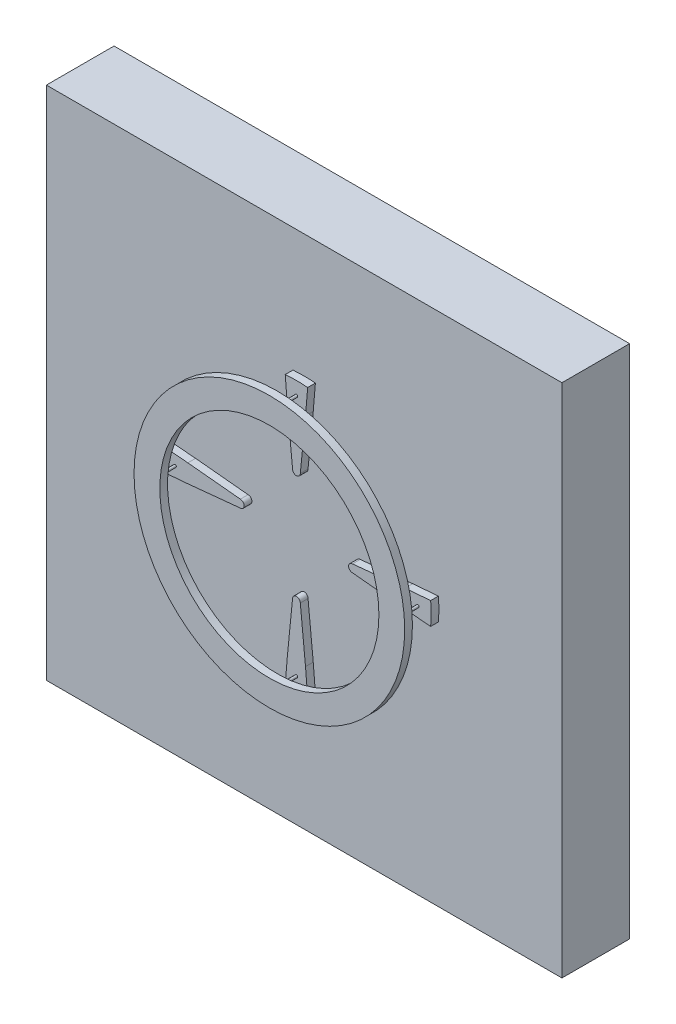
SolidWorks part; units mm, degrees
ref_plane "前基準面" through (0, 0, 0) normal (0, 0, 1) x (1, 0, 0)
ref_plane "上基準面" through (0, 0, 0) normal (0, 1, 0) x (1, 0, 0)
ref_plane "右基準面" through (0, 0, 0) normal (1, 0, 0) x (0, 0, -1)
sketch "草圖1" plane through (0, 0, 0) normal (0, 0, 1) x (1, 0, 0)
  line L0 (-0.03, 0.435) -> (-0.0704, 0.8425)
  line L1 (0, 0.435) -> (0, 0.8542) construction
  line L2 (0.03, 0.435) -> (0.0704, 0.8425)
  line L3 (0.435, 0.03) -> (0.8425, 0.0704)
  line L4 (0.435, -0.03) -> (0.8425, -0.0704)
  line L5 (0.03, -0.435) -> (0.0704, -0.8425)
  line L6 (-0.03, -0.435) -> (-0.0704, -0.8425)
  line L7 (-0.435, -0.03) -> (-0.8425, -0.0704)
  line L8 (-0.435, 0.03) -> (-0.8425, 0.0704)
  line L9 (-0.0704, 0.8425) -> (-0.087, 1.0414)
  line L10 (0.0704, 0.8425) -> (0.087, 1.0414)
  line L11 (0.8425, 0.0704) -> (1.0414, 0.087)
  line L12 (0.8425, -0.0704) -> (1.0414, -0.087)
  line L13 (-0.0704, -0.8425) -> (-0.087, -1.0414)
  line L14 (0.0704, -0.8425) -> (0.087, -1.0414)
  line L15 (-0.8425, 0.0704) -> (-1.0414, 0.087)
  line L16 (-0.8425, -0.0704) -> (-1.0414, -0.087)
  circle A0 centre (0, 0) radius 0.405
  arc A2 (-0.03, 0.435) -> (0.03, 0.435) centre (0, 0.435) ccw
  arc A4 (0.435, 0.03) -> (0.435, -0.03) centre (0.435, 0) ccw
  arc A6 (0.03, -0.435) -> (-0.03, -0.435) centre (0, -0.435) ccw
  arc A8 (-0.435, -0.03) -> (-0.435, 0.03) centre (-0.435, 0) ccw
  arc A9 (0.0704, 0.8425) -> (-0.0704, 0.8425) centre (0, 0) ccw
  arc A10 (0.087, 1.0414) -> (-0.087, 1.0414) centre (0, 0) ccw
  arc A11 (-1.0414, 0.087) -> (-1.0414, -0.087) centre (0, 0) ccw
  arc A12 (-0.8425, 0.0704) -> (-0.8425, -0.0704) centre (0, 0) ccw
  arc A13 (-0.0704, -0.8425) -> (0.0704, -0.8425) centre (0, 0) ccw
  arc A14 (-0.087, -1.0414) -> (0.087, -1.0414) centre (0, 0) ccw
  arc A15 (1.0414, -0.087) -> (1.0414, 0.087) centre (0, 0) ccw
  arc A16 (0.8425, -0.0704) -> (0.8425, 0.0704) centre (0, 0) ccw
  point P27 (0, 0)
  dimension "D1" = 5.66
  dimension "D2" = 4
extrude "填料-伸長1" add sketch "草圖1" along normal blind 0.06
sketch "草圖2" plane through (0, 0, 0.06) normal (0, 0, 1) x (1, 0, 0)
  line L0 (0.9419, 0.0787) -> (0.9419, -0.1053) construction
  line L1 (0.8425, 0.0704) -> (1.0414, 0.087) construction
  line L2 (1.05, 0) -> (0.6277, 0) construction
  line L3 (0.8425, -0.0704) -> (1.0414, -0.087) construction
  circle A0 centre (0, 0) radius 0.85
  circle A1 centre (0, 0) radius 1.05
  circle A3 centre (0.9419, 0) radius 0.07
  circle A4 centre (0, -0.9419) radius 0.07
  circle A5 centre (-0.9419, 0) radius 0.07
  circle A6 centre (0, 0.9419) radius 0.07
  circle A7 centre (0.9419, 0) radius 0.01
  circle A8 centre (0, -0.9419) radius 0.01
  circle A9 centre (-0.9419, 0) radius 0.01
  circle A10 centre (0, 0.9419) radius 0.01
  point P10 (0.9419, 0)
  point P11 (0.847, 0.0708)
  point P12 (0.847, -0.0708)
  point P26 (0, 0)
  point P34 (0, 0)
  dimension "D1" = 4
  dimension "D2" = 4
extrude "填料-伸長2" add sketch "草圖2" along normal blind 0.15 contours A7 | A10 | A9 | A8
sketch "草圖3" plane through (0, 0, 0.21) normal (0, 0, 1) x (1, 0, 0)
  circle A0 centre (0, 0) radius 0.85
  circle A1 centre (0, 0) radius 1.05
extrude "填料-伸長3" add sketch "草圖3" along normal blind 0.06
sketch "草圖4" plane through (0, 0, 0) normal (0, 0, -1) x (-1, 0, 0)
  line L1 (2, -2) -> (-2, -2)
  line L2 (2, -2) -> (2, 2)
  line L3 (2, 2) -> (-2, 2)
  line L4 (-2, -2) -> (-2, 2)
  line L5 (2, -2) -> (-2, 2) construction
  line L6 (2, 2) -> (-2, -2) construction
  point P0 (0, 0)
extrude "填料-伸長5" add sketch "草圖4" along normal blind 0.525
